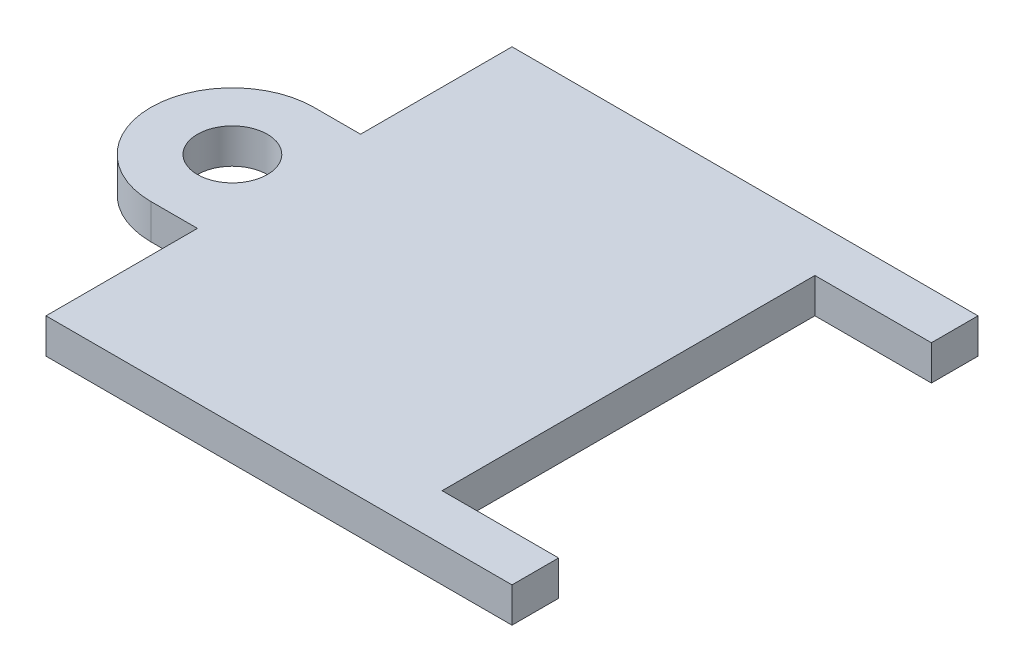
SolidWorks part; units mm, degrees
ref_plane "Front Plane" through (0, 0, 0) normal (0, 0, 1) x (1, 0, 0)
ref_plane "Top Plane" through (0, 0, 0) normal (0, 1, 0) x (1, 0, 0)
ref_plane "Right Plane" through (0, 0, 0) normal (1, 0, 0) x (0, 0, -1)
sketch "Sketch2" plane through (0, 0, 0) normal (0, 1, 0) x (1, 0, 0)
  line L0 (15, 18) -> (15, 2)
  line L1 (0, 0) -> (15, 0)
  line L2 (0, 0) -> (0, 6.5)
  line L3 (0, 20) -> (15, 20)
  line L5 (-2, 13.5) -> (0, 13.5)
  line L6 (-2, 13.5) -> (-2, 6.5) construction
  line L7 (-2, 6.5) -> (0, 6.5)
  line L8 (0, 13.5) -> (0, 20)
  line L9 (15, 10) -> (-9.2853, 10) construction
  line L10 (15, 20) -> (20, 20)
  line L11 (20, 20) -> (20, 18)
  line L12 (20, 18) -> (15, 18)
  line L13 (15, 0) -> (20, 0)
  line L14 (20, 0) -> (20, 2)
  line L15 (20, 2) -> (15, 2)
  circle A0 centre (-2, 10) radius 1.5
  arc A1 (-2, 13.5) -> (-2, 6.5) centre (-2, 10) ccw
  dimension "D3" = 3
  dimension "D5" = 7
  dimension "D1" = 15
  dimension "D2" = 20
  dimension "D4" = 2
  dimension "D6" = 5
  dimension "D7" = 2
  dimension "D8" = 5
  dimension "D9" = 2
extrude "Boss-Extrude1" add sketch "Sketch2" along normal blind 1.5
sketch "Sketch3" plane through (0, 0, 0) normal (0, -1, 0) x (1, 0, 0)
  line L0 (2.2, -2.2) -> (12.8, -2.2)
  line L1 (12.8, -2.2) -> (12.8, -17.8)
  line L2 (12.8, -17.8) -> (2.2, -17.8)
  line L4 (2.2, -2.2) -> (2.2, -17.8)
  line L5 (0, 0) -> (15, 0) construction
  line L6 (0, -20) -> (15, -20) construction
  line L7 (0, -13.5) -> (0, -20) construction
  line L8 (15, -18) -> (15, -2) construction
  dimension "D1" = 2.2
  dimension "D2" = 2.2
  dimension "D3" = 2.2
  dimension "D4" = 2.2
extrude "Boss-Extrude2" add sketch "Sketch3" along normal blind 1.5
